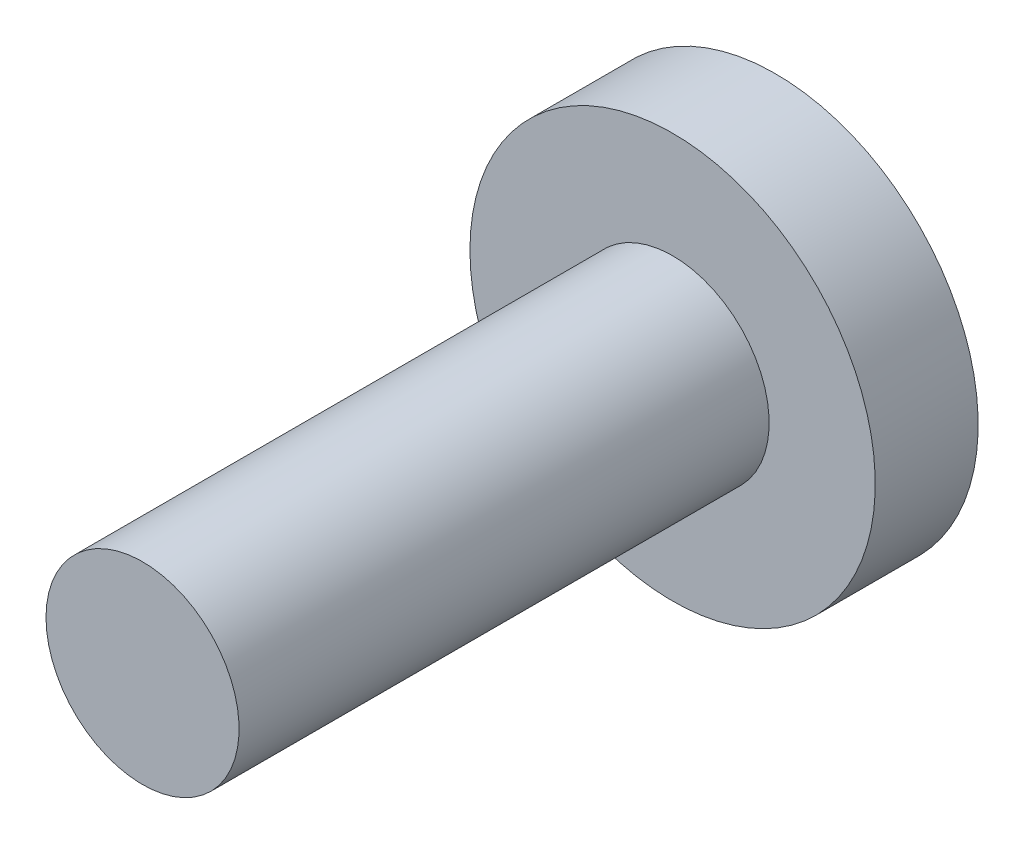
SolidWorks part; units mm, degrees
ref_plane "Front" through (0, 0, 0) normal (0, 0, 1) x (1, 0, 0)
ref_plane "Top" through (0, 0, 0) normal (0, 1, 0) x (1, 0, 0)
ref_plane "Right" through (0, 0, 0) normal (1, 0, 0) x (0, 0, -1)
sketch "Sketch2" plane through (0, 0, 0) normal (0, 1, 0) x (1, 0, 0)
  line L0 (0, 0) -> (0, -32.4825)
  line L1 (0, -32.4825) -> (11.9126, -32.4825)
  line L2 (11.9126, -32.4825) -> (11.9126, 32.9225)
  line L3 (11.9126, 32.9225) -> (25.0063, 32.9225)
  line L4 (25.0063, 32.9225) -> (25.0063, 45.6225)
  line L5 (25.0063, 45.6225) -> (0, 45.6225)
  line L6 (0, 45.6225) -> (0, 0)
  dimension "D1" = 11.9126
  dimension "D2" = 65.405
  dimension "D3" = 25.0063
  dimension "D4" = 12.7
revolve "Revolve1" add sketch "Sketch2" angle 360 about L6
